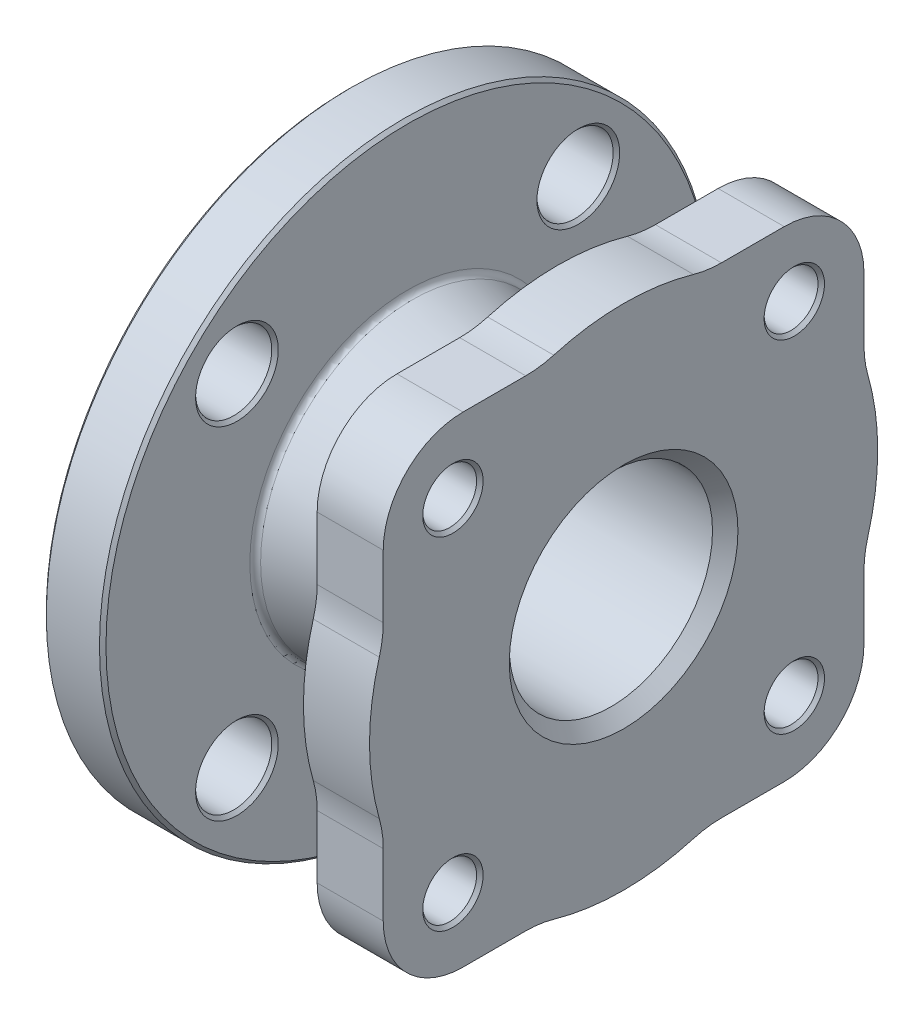
SolidWorks part; units mm, degrees
ref_plane "Alzado" through (0, 0, 0) normal (0, 0, 1) x (1, 0, 0)
ref_plane "Planta" through (0, 0, 0) normal (0, 1, 0) x (1, 0, 0)
ref_plane "Vista lateral" through (0, 0, 0) normal (1, 0, 0) x (0, 0, -1)
sketch "Croquis1" plane through (0, 0, 0) normal (0, 0, 1) x (1, 0, 0)
  line L0 (0, 25.4) -> (53.975, 25.4)
  line L1 (53.975, 25.4) -> (53.975, 47.625)
  line L2 (53.975, 47.625) -> (52.3748, 46.0248)
  line L3 (52.3748, 46.0248) -> (52.3748, 34.29)
  line L4 (52.3748, 34.29) -> (34.925, 34.29)
  line L5 (34.925, 34.29) -> (16.51, 38.2042)
  line L6 (16.51, 38.2042) -> (16.51, 76.2)
  line L7 (16.51, 76.2) -> (1.6002, 76.2)
  line L8 (1.6002, 76.2) -> (1.6002, 47.6377)
  line L9 (1.6002, 47.6377) -> (0, 46.0375)
  line L10 (0, 46.0375) -> (0, 25.4)
  line L11 (0, 25.4) -> (0, 0) construction
  line L12 (0, 0) -> (54.102, 0) construction
  dimension "D1" = 53.975
  dimension "D2" = 50.8
  dimension "D3" = 95.25
  dimension "D4" = 1.6002
  dimension "D5" = 45
  dimension "D6" = 68.58
  dimension "D7" = 12
  dimension "D8" = 34.925
  dimension "D9" = 16.51
  dimension "D10" = 1.6002
  dimension "D11" = 45
  dimension "D12" = 152.4
  dimension "D13" = 92.075
revolve "Revolución1" add sketch "Croquis1" angle 360 about L12
sketch "Croquis2" plane through (53.975, 0, 0) normal (1, 0, 0) x (0, 0, -1)
  line L0 (0, 25.4) -> (0, 0) construction
  line L1 (0, 0) -> (-42.6562, 42.6562) construction
  line L2 (-42.6562, 42.6562) -> (-53.8815, 53.8815) construction
  line L3 (0, 0) -> (42.6562, 42.6562) construction
  line L4 (0, 0) -> (42.6562, -42.6562) construction
  line L5 (0, 0) -> (-42.6562, -42.6562) construction
  line L6 (-40.132, 60.071) -> (-40.132, 40.132) construction
  line L7 (-40.132, 40.132) -> (-60.071, 40.132) construction
  line L8 (-60.071, 40.132) -> (-60.071, 24.4524)
  line L9 (-40.132, 60.071) -> (-24.4524, 60.071)
  line L10 (40.132, 60.071) -> (24.4524, 60.071)
  line L11 (60.071, 40.132) -> (60.071, 24.4524)
  line L12 (60.071, -40.132) -> (60.071, -24.4524)
  line L13 (40.132, -60.071) -> (24.4524, -60.071)
  line L14 (-40.132, -60.071) -> (-24.4524, -60.071)
  line L15 (-60.071, -40.132) -> (-60.071, -24.4524)
  arc A0 (-61.0507, 17.466) -> (-61.0507, -17.466) centre (0, 0) ccw
  circle A1 centre (0, 0) radius 60.325 construction
  arc A2 (-17.466, -61.0507) -> (17.466, -61.0507) centre (0, 0) ccw
  arc A3 (61.0507, -17.466) -> (61.0507, 17.466) centre (0, 0) ccw
  circle A6 centre (0, 0) radius 25.4 construction
  circle A7 centre (0, 0) radius 76.2 construction
  arc A8 (-40.132, 60.071) -> (-60.071, 40.132) centre (-40.132, 40.132) ccw
  arc A9 (60.071, 40.132) -> (40.132, 60.071) centre (40.132, 40.132) ccw
  arc A10 (40.132, -60.071) -> (60.071, -40.132) centre (40.132, -40.132) ccw
  arc A11 (-60.071, -40.132) -> (-40.132, -60.071) centre (-40.132, -40.132) ccw
  arc A12 (17.466, 61.0507) -> (-17.466, 61.0507) centre (0, 0) ccw
  arc A13 (-24.4524, 60.071) -> (-17.466, 61.0507) centre (-24.4524, 85.471) ccw
  arc A14 (24.4524, 60.071) -> (17.466, 61.0507) centre (24.4524, 85.471) cw
  arc A15 (60.071, 24.4524) -> (61.0507, 17.466) centre (85.471, 24.4524) ccw
  arc A16 (60.071, -24.4524) -> (61.0507, -17.466) centre (85.471, -24.4524) cw
  arc A17 (24.4524, -60.071) -> (17.466, -61.0507) centre (24.4524, -85.471) ccw
  arc A18 (-24.4524, -60.071) -> (-17.466, -61.0507) centre (-24.4524, -85.471) cw
  arc A19 (-60.071, -24.4524) -> (-61.0507, -17.466) centre (-85.471, -24.4524) ccw
  arc A20 (-60.071, 24.4524) -> (-61.0507, 17.466) centre (-85.471, 24.4524) cw
  circle A21 centre (-42.6562, 42.6562) radius 6.731
  circle A22 centre (42.6562, 42.6562) radius 6.731
  circle A23 centre (42.6562, -42.6562) radius 6.731
  circle A24 centre (-42.6562, -42.6562) radius 6.731
  circle A26 centre (0, 0) radius 25.4
  point P25 (0, 0)
  point P43 (0, 0)
  dimension "D1" = 127
  dimension "D2" = 120.65
  dimension "D4" = 39.878
  dimension "D9" = 25.4
  dimension "D10" = 13.462
  dimension "D3" = 45
  dimension "D5" = 40.132
  dimension "D6" = 40.132
  dimension "D7" = 4
  dimension "D8" = 4
extrude "Saliente-Extruir1" add sketch "Croquis2" along normal blind 16.51
sketch "Croquis3" plane through (1.6002, 0, 0) normal (-1, 0, 0) x (0, 0, 1)
  line L0 (0, 25.4) -> (0, 0)
  line L1 (0, 0) -> (-42.6562, 42.6562) construction
  line L2 (0, 0) -> (42.6562, 42.6562) construction
  line L3 (0, 0) -> (42.6562, -42.6562) construction
  line L4 (0, 0) -> (-42.6562, -42.6562) construction
  circle A0 centre (0, 0) radius 60.325 construction
  circle A1 centre (0, 0) radius 25.4
  circle A3 centre (0, 0) radius 25.4
  circle A5 centre (-42.6562, 42.6562) radius 9.525
  circle A9 centre (42.6562, 42.6562) radius 9.525
  circle A12 centre (42.6562, -42.6562) radius 9.525
  circle A14 centre (-42.6562, -42.6562) radius 9.525
  point P14 (0, 0)
  dimension "D2" = 19.05
  dimension "D1" = 0
  dimension "D3" = 4
extrude "Cortar-Extruir1" cut sketch "Croquis3" against normal up to next contours A5 | A9 | A12 | A14
chamfer "Chaflán1" distance 0.8128 angle 45 18 edges at (16.51, -42.6562, -33.1312) (1.6002, -42.6562, -33.1312) (53.975, 42.6562, 35.9252) (70.485, 42.6562, 35.9252) (53.975, 42.6562, -49.3872) (70.485, 42.6562, -49.3872) (53.975, -42.6562, -49.3872) (70.485, -42.6562, -49.3872) (53.975, -42.6562, 35.9252) (70.485, -42.6562, 35.9252) (16.51, -42.6562, 52.1812) (1.6002, -42.6562, 52.1812) (16.51, 42.6562, -33.1312) (1.6002, 42.6562, -33.1312) (16.51, 42.6562, 52.1812) (1.6002, 42.6562, 52.1812) (16.51, 0, 76.2) (1.6002, 0, 76.2)
chamfer "Chaflán2" distance 3.175 angle 45 2 edges at (70.485, 0, -25.4) (0, 0, 25.4)
fillet "Redondeo1" radius 1.524 2 edges at (52.3748, 0, 34.29) (16.51, 0, 38.2042)
sketch "Croquis4" plane through (70.485, 0, 0) normal (1, 0, 0) x (0, 0, -1)
  line L8 (-24.4524, 60.071) -> (-40.132, 60.071)
  line L9 (-60.071, 40.132) -> (-60.071, 24.4524)
  line L10 (-60.071, -24.4524) -> (-60.071, -40.132)
  line L11 (-40.132, -60.071) -> (-24.4524, -60.071)
  line L12 (24.4524, -60.071) -> (40.132, -60.071)
  line L13 (60.071, -40.132) -> (60.071, -24.4524)
  line L14 (60.071, 24.4524) -> (60.071, 40.132)
  line L15 (40.132, 60.071) -> (24.4524, 60.071)
  line L16 (-24.4524, 60.071) -> (-40.132, 60.071)
  line L17 (-60.071, 40.132) -> (-60.071, 24.4524)
  line L18 (-60.071, -24.4524) -> (-60.071, -40.132)
  line L19 (-40.132, -60.071) -> (-24.4524, -60.071)
  line L20 (24.4524, -60.071) -> (40.132, -60.071)
  line L21 (60.071, -40.132) -> (60.071, -24.4524)
  line L22 (60.071, 24.4524) -> (60.071, 40.132)
  line L23 (40.132, 60.071) -> (24.4524, 60.071)
  circle A0 centre (0, 0) radius 25.4 construction
  circle A1 centre (42.6562, -42.6562) radius 6.731 construction
  circle A2 centre (-42.6562, -42.6562) radius 6.731 construction
  circle A3 centre (42.6562, 42.6562) radius 6.731 construction
  circle A4 centre (-42.6562, 42.6562) radius 6.731 construction
  circle A5 centre (0, 0) radius 25.4
  circle A6 centre (42.6562, -42.6562) radius 6.731
  circle A7 centre (-42.6562, -42.6562) radius 6.731
  circle A8 centre (42.6562, 42.6562) radius 6.731
  circle A9 centre (-42.6562, 42.6562) radius 6.731
  arc A16 (-24.4524, 60.071) -> (-17.466, 61.0507) centre (-24.4524, 85.471) ccw
  arc A17 (-40.132, 60.071) -> (-60.071, 40.132) centre (-40.132, 40.132) ccw
  arc A18 (-61.0507, 17.466) -> (-60.071, 24.4524) centre (-85.471, 24.4524) ccw
  arc A19 (-61.0507, 17.466) -> (-61.0507, -17.466) centre (0, 0) ccw
  arc A20 (-60.071, -24.4524) -> (-61.0507, -17.466) centre (-85.471, -24.4524) ccw
  arc A21 (-60.071, -40.132) -> (-40.132, -60.071) centre (-40.132, -40.132) ccw
  arc A22 (-17.466, -61.0507) -> (-24.4524, -60.071) centre (-24.4524, -85.471) ccw
  arc A23 (-17.466, -61.0507) -> (17.466, -61.0507) centre (0, 0) ccw
  arc A24 (24.4524, -60.071) -> (17.466, -61.0507) centre (24.4524, -85.471) ccw
  arc A25 (40.132, -60.071) -> (60.071, -40.132) centre (40.132, -40.132) ccw
  arc A26 (61.0507, -17.466) -> (60.071, -24.4524) centre (85.471, -24.4524) ccw
  arc A27 (61.0507, -17.466) -> (61.0507, 17.466) centre (0, 0) ccw
  arc A28 (60.071, 24.4524) -> (61.0507, 17.466) centre (85.471, 24.4524) ccw
  arc A29 (60.071, 40.132) -> (40.132, 60.071) centre (40.132, 40.132) ccw
  arc A30 (17.466, 61.0507) -> (24.4524, 60.071) centre (24.4524, 85.471) ccw
  arc A31 (17.466, 61.0507) -> (-17.466, 61.0507) centre (0, 0) ccw
  arc A32 (-24.4524, 60.071) -> (-17.466, 61.0507) centre (-24.4524, 85.471) ccw
  arc A33 (-40.132, 60.071) -> (-60.071, 40.132) centre (-40.132, 40.132) ccw
  arc A34 (-61.0507, 17.466) -> (-60.071, 24.4524) centre (-85.471, 24.4524) ccw
  arc A35 (-61.0507, 17.466) -> (-61.0507, -17.466) centre (0, 0) ccw
  arc A36 (-60.071, -24.4524) -> (-61.0507, -17.466) centre (-85.471, -24.4524) ccw
  arc A37 (-60.071, -40.132) -> (-40.132, -60.071) centre (-40.132, -40.132) ccw
  arc A38 (-17.466, -61.0507) -> (-24.4524, -60.071) centre (-24.4524, -85.471) ccw
  arc A39 (-17.466, -61.0507) -> (17.466, -61.0507) centre (0, 0) ccw
  arc A40 (24.4524, -60.071) -> (17.466, -61.0507) centre (24.4524, -85.471) ccw
  arc A41 (40.132, -60.071) -> (60.071, -40.132) centre (40.132, -40.132) ccw
  arc A42 (61.0507, -17.466) -> (60.071, -24.4524) centre (85.471, -24.4524) ccw
  arc A43 (61.0507, -17.466) -> (61.0507, 17.466) centre (0, 0) ccw
  arc A44 (60.071, 24.4524) -> (61.0507, 17.466) centre (85.471, 24.4524) ccw
  arc A45 (60.071, 40.132) -> (40.132, 60.071) centre (40.132, 40.132) ccw
  arc A46 (17.466, 61.0507) -> (24.4524, 60.071) centre (24.4524, 85.471) ccw
  arc A47 (17.466, 61.0507) -> (-17.466, 61.0507) centre (0, 0) ccw
  dimension "D1" = 0
extrude "Saliente-Extruir2" add sketch "Croquis4" along normal blind 16.51 separate body
sketch "Croquis5" plane through (0, 0, 0) normal (0, 0, 1) x (1, 0, 0)
  line L0 (0, 0) -> (187.7004, 0) construction
  line L1 (86.995, -25.4) -> (156.845, -25.4)
  line L2 (86.995, -24.4524) -> (86.995, -40.132) construction
  line L3 (156.845, -25.4) -> (156.845, -38.1)
  line L4 (156.845, -38.1) -> (141.097, -38.1)
  line L5 (141.097, -38.1) -> (100.143, -49.0736)
  line L6 (86.995, -60.071) -> (86.995, -40.132) construction
  line L7 (86.995, -50.8046) -> (107.3647, -50.8046) construction
  line L8 (86.995, -25.4) -> (86.995, -50.8046)
  arc A0 (100.143, -49.0736) -> (86.995, -50.8046) centre (86.995, -0.0046) cw
  dimension "D5" = 50.8
  dimension "D1" = 50.8
  dimension "D2" = 76.2
  dimension "D3" = 15.748
  dimension "D4" = 15
  dimension "D6" = 69.85
revolve "Revolución2" add sketch "Croquis5" angle 360 about L0
sketch "Croquis6" plane through (156.845, 0, 0) normal (1, 0, 0) x (0, 0, -1)
  circle A0 centre (0, 0) radius 76.2 construction
  circle A1 centre (0, 0) radius 76.2
  circle A2 centre (42.6562, -42.6562) radius 9.525 construction
  circle A3 centre (-42.6562, -42.6562) radius 9.525 construction
  circle A4 centre (42.6562, 42.6562) radius 9.525 construction
  circle A5 centre (-42.6562, 42.6562) radius 9.525 construction
  circle A6 centre (42.6562, -42.6562) radius 9.525
  circle A7 centre (-42.6562, -42.6562) radius 9.525
  circle A8 centre (42.6562, 42.6562) radius 9.525
  circle A9 centre (-42.6562, 42.6562) radius 9.525
  circle A10 centre (0, 0) radius 25.4 construction
  circle A11 centre (0, 0) radius 25.4
extrude "Saliente-Extruir3" add sketch "Croquis6" along normal blind 16.51
delete or keep bodies "Sólido-Eliminar/Conservar 2" type delete bodies bodies 104 105 106
